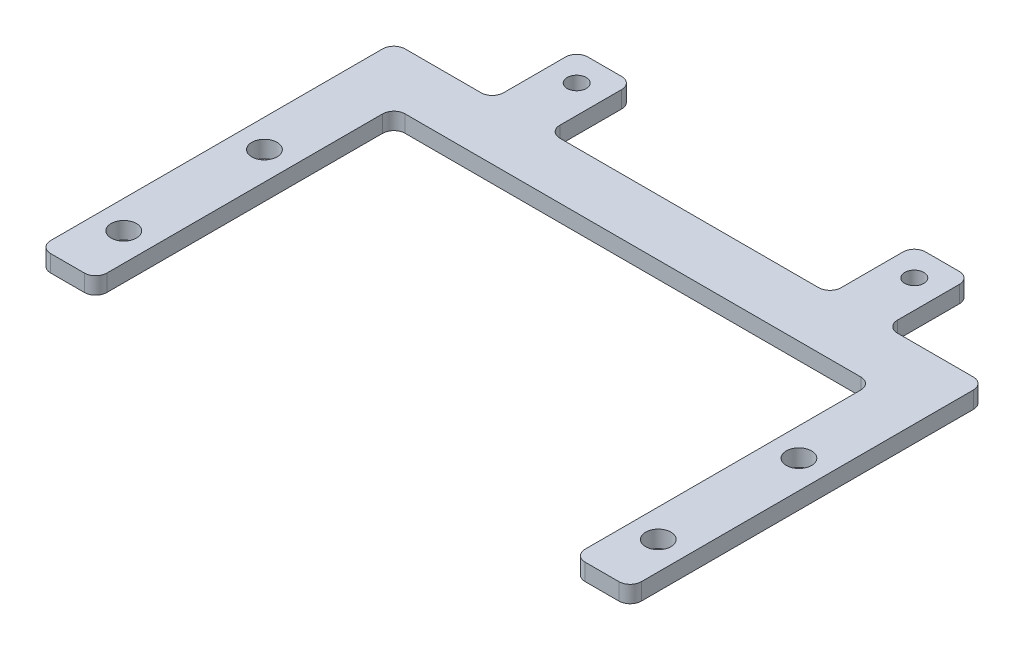
SolidWorks part; units mm, degrees
material "201 退火不锈钢 (SS)"
ref_plane "前视" through (0, 0, 0) normal (0, 0, 1) x (1, 0, 0)
ref_plane "上视" through (0, 0, 0) normal (0, 1, 0) x (1, 0, 0)
ref_plane "右视" through (0, 0, 0) normal (1, 0, 0) x (0, 0, -1)
sketch "草图1" plane through (0, 0, 0) normal (0, 1, 0) x (1, 0, 0)
  line L0 (42.5, -31.5) -> (52.5, -31.5)
  line L1 (-52.5, -31.5) -> (-42.5, -31.5)
  line L2 (-52.5, -31.5) -> (-52.5, 31.5)
  line L3 (-52.5, 31.5) -> (-35, 31.5)
  line L4 (52.5, -31.5) -> (52.5, 31.5)
  line L5 (-52.5, -31.5) -> (52.5, 31.5) construction
  line L6 (-52.5, 31.5) -> (52.5, -31.5) construction
  line L7 (-25, 46.5) -> (-25, 31.5)
  line L8 (-42.5, -31.5) -> (-42.5, 21.5)
  line L9 (-42.5, 21.5) -> (42.5, 21.5)
  line L10 (42.5, -31.5) -> (42.5, 21.5)
  line L11 (-42.5, -31.5) -> (42.5, 21.5) construction
  line L12 (-42.5, 21.5) -> (42.5, -31.5) construction
  line L13 (-25, 31.5) -> (25, 31.5)
  line L14 (-35, 31.5) -> (-35, 46.5)
  line L15 (-35, 46.5) -> (-25, 46.5)
  line L16 (35, 31.5) -> (35, 46.5)
  line L17 (-35, 31.5) -> (35, 46.5) construction
  line L18 (-35, 46.5) -> (35, 31.5) construction
  line L19 (0, 62.9533) -> (0, 9.4856) construction
  line L20 (25, 46.5) -> (25, 31.5)
  line L21 (25, 46.5) -> (35, 46.5)
  line L22 (35, 31.5) -> (52.5, 31.5)
  point P0 (0, 0)
  point P5 (0, -5)
  point P11 (0, 39)
  dimension "D1" = 105
  dimension "D2" = 63
  dimension "D3" = 85
  dimension "D4" = 53
  dimension "D5" = 15
  dimension "D6" = 70
  dimension "D7" = 10
extrude "凸台-拉伸1" add sketch "草图1" along normal blind 3
sketch "草图2" plane through (0, 3, 0) normal (0, 1, 0) x (1, 0, 0)
  line L0 (-52.5, -31.5) -> (-42.5, -31.5) construction
  line L1 (-35, 31.5) -> (-52.5, 31.5) construction
  line L2 (0, 45.5086) -> (0, -17.3633) construction
  circle A0 centre (-47.5, -21.5) radius 2.25
  circle A1 centre (-47.5, 3.5) radius 2.25
  circle A2 centre (-30, 41.5) radius 1.7
  circle A3 centre (47.5, -21.5) radius 2.25
  circle A4 centre (47.5, 3.5) radius 2.25
  circle A5 centre (30, 41.5) radius 1.7
  dimension "D1" = 4.5
  dimension "D2" = 10
  dimension "D3" = 25
  dimension "D4" = 4.5
  dimension "D5" = 10
  dimension "D6" = 3.4
extrude "切除-拉伸1" cut sketch "草图2" against normal blind 3
fillet "圆角1" radius 2 16 edges at (-52.5, 1.5, 31.5) (-42.5, 1.5, 31.5) (42.5, 1.5, -21.5) (42.5, 1.5, 31.5) (52.5, 1.5, 31.5) (52.5, 1.5, -31.5) (35, 1.5, -31.5) (35, 1.5, -46.5) (25, 1.5, -46.5) (25, 1.5, -31.5) (-35, 1.5, -46.5) (-25, 1.5, -46.5) (-25, 1.5, -31.5) (-35, 1.5, -31.5) (-52.5, 1.5, -31.5) (-42.5, 1.5, -21.5)
